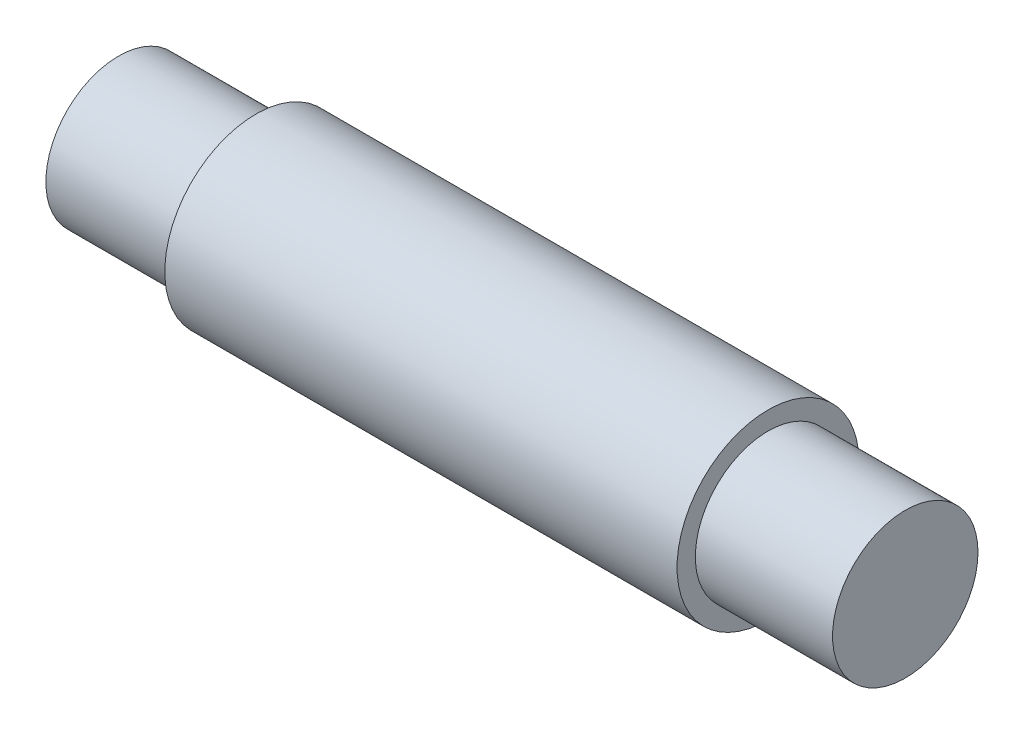
SolidWorks part; units mm, degrees
material "AISI 304"
ref_plane "Front Plane" through (0, 0, 0) normal (0, 0, 1) x (1, 0, 0)
ref_plane "Top Plane" through (0, 0, 0) normal (0, 1, 0) x (1, 0, 0)
ref_plane "Right Plane" through (0, 0, 0) normal (1, 0, 0) x (0, 0, -1)
sketch "Croquis1" plane through (0, 0, 0) normal (0, 0, 1) x (1, 0, 0)
  line L0 (64.0222, 0) -> (-64.0222, 0) construction
  line L1 (43, 0) -> (-43, 0)
  line L2 (-43, 0) -> (-43, 7.95)
  line L3 (-43, 7.95) -> (-28, 7.95)
  line L4 (-28, 7.95) -> (-28, 9.95)
  line L5 (-28, 9.95) -> (28, 9.95)
  line L6 (28, 9.95) -> (28, 7.95)
  line L7 (28, 7.95) -> (43, 7.95)
  line L8 (43, 7.95) -> (43, 0)
  point P4 (0, 0)
  point P7 (0, 0)
  dimension "D1" = 86
  dimension "D2" = 15.9
  dimension "D3" = 19.9
  dimension "D4" = 56
  dimension "D5" = 15
revolve "Revolución1" add sketch "Croquis1" angle 360 about L0
